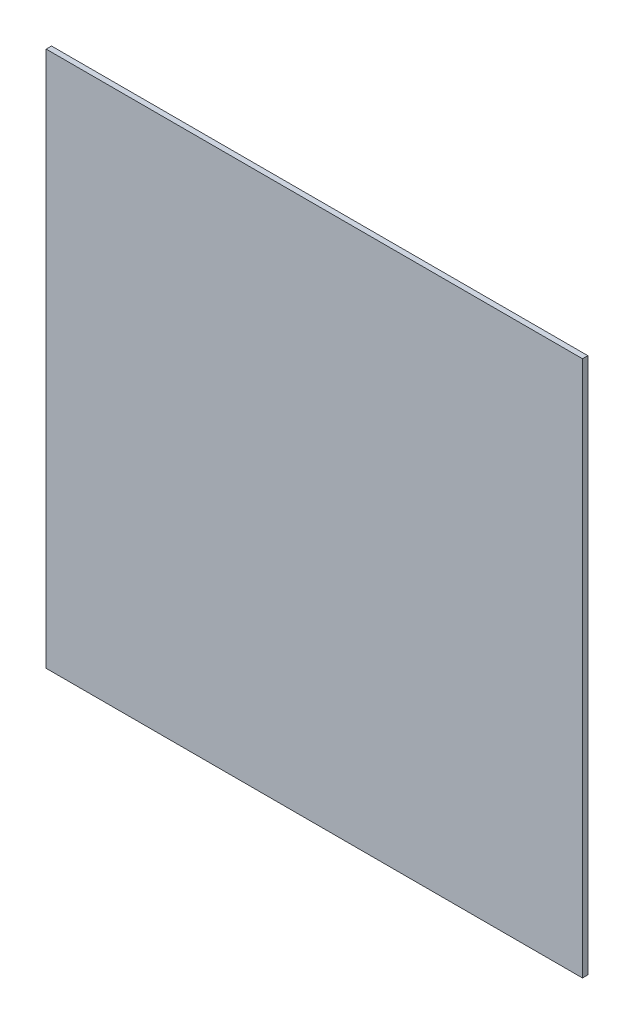
SolidWorks part; units mm, degrees
material "炭素鋼(普通)"
ref_plane "正面" through (0, 0, 0) normal (0, 0, 1) x (1, 0, 0)
ref_plane "平面" through (0, 0, 0) normal (0, 1, 0) x (1, 0, 0)
ref_plane "右側面" through (0, 0, 0) normal (1, 0, 0) x (0, 0, -1)
sketch "ｽｹｯﾁ1" plane through (0, 0, 0) normal (0, 0, 1) x (1, 0, 0)
  line L1 (-5000, -5000) -> (5000, -5000)
  line L2 (-5000, -5000) -> (-5000, 5000)
  line L3 (-5000, 5000) -> (5000, 5000)
  line L4 (5000, -5000) -> (5000, 5000)
  line L5 (-5000, -5000) -> (5000, 5000) construction
  line L6 (-5000, 5000) -> (5000, -5000) construction
  point P0 (0, 0)
extrude "ﾎﾞｽ - 押し出し1" add sketch "ｽｹｯﾁ1" along normal blind 100
